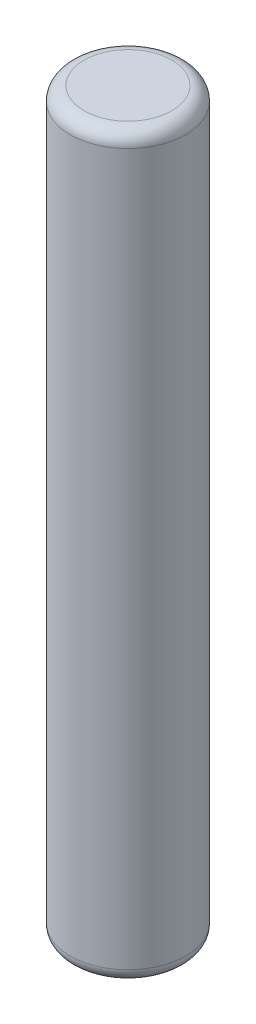
SolidWorks part; units mm, degrees
ref_plane "Front Plane" through (0, 0, 0) normal (0, 0, 1) x (1, 0, 0)
ref_plane "Top Plane" through (0, 0, 0) normal (0, 1, 0) x (1, 0, 0)
ref_plane "Right Plane" through (0, 0, 0) normal (1, 0, 0) x (0, 0, -1)
sketch "Sketch1" plane through (0, 0, 0) normal (0, 1, 0) x (1, 0, 0)
  circle A0 centre (0, 0) radius 1.25
  dimension "D1" = 2.5
extrude "profile_extrude" add sketch "Sketch1" along normal blind 16
fillet "dovel _filet" radius 0.3 2 edges at (0, 0, 1.25) (0, 16, 1.25)
